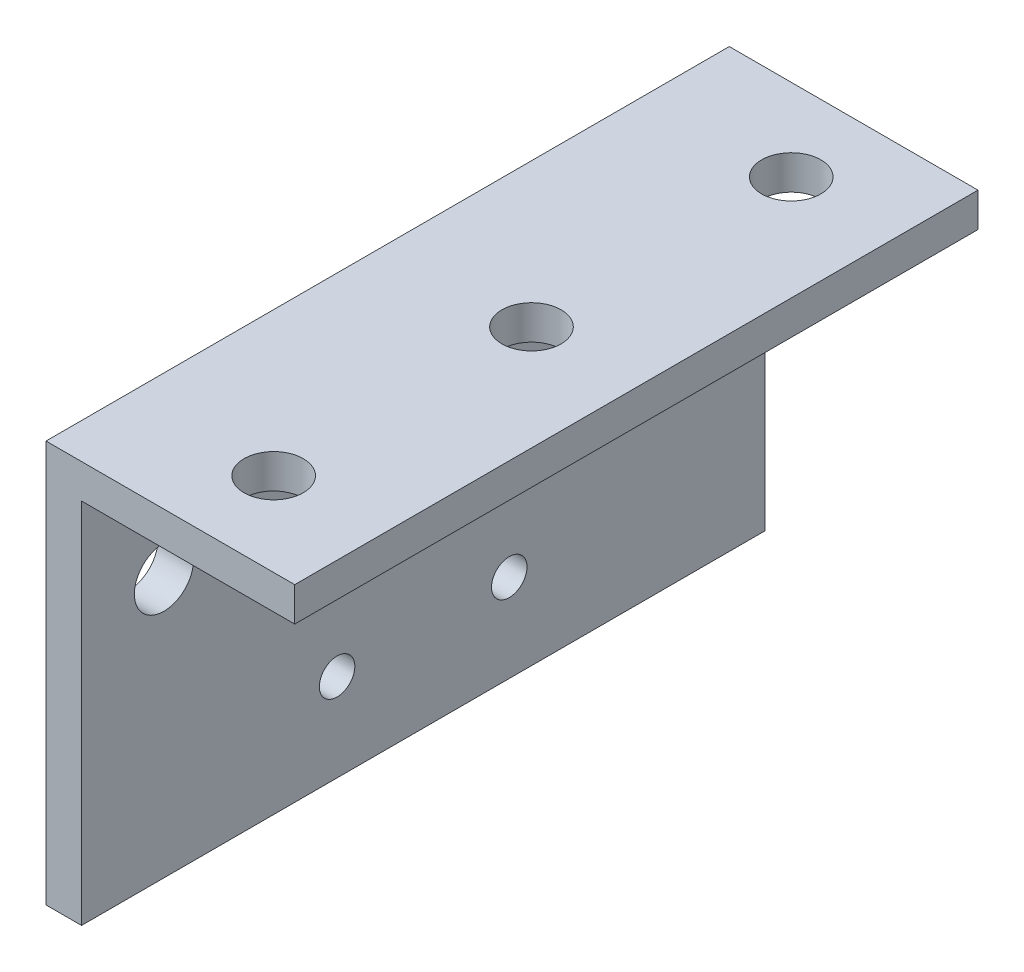
SolidWorks part; units mm, degrees
material "6061 Alloy"
ref_plane "Front Plane" through (0, 0, 0) normal (0, 0, 1) x (1, 0, 0)
ref_plane "Top Plane" through (0, 0, 0) normal (0, 1, 0) x (1, 0, 0)
ref_plane "Right Plane" through (0, 0, 0) normal (1, 0, 0) x (0, 0, -1)
sketch "Sketch1" plane through (0, 0, 0) normal (0, 0, 1) x (1, 0, 0)
  line L0 (0, 0) -> (0, 37.338)
  line L1 (0, 37.338) -> (23.114, 37.338)
  line L2 (23.114, 37.338) -> (23.114, 34.163)
  line L3 (0, 0) -> (3.302, 0)
  line L4 (3.302, 0) -> (3.302, 34.163)
  line L5 (3.302, 34.163) -> (23.114, 34.163)
  dimension "D1" = 37.338
  dimension "D2" = 23.114
  dimension "D3" = 3.175
extrude "Boss-Extrude1" add sketch "Sketch1" along normal blind 63.5
sketch "Sketch21" plane through (0, 0, 0) normal (-1, 0, 0) x (0, 0, 1)
  line L0 (31.75, 0) -> (31.75, 37.338) construction
  line L1 (63.5, 0) -> (0, 0) construction
  line L2 (63.5, 37.338) -> (0, 37.338) construction
  point P3 (31.75, 18.669)
sketch "Sketch28" plane through (0, 37.338, 0) normal (0, 1, 0) x (1, 0, 0)
  line L0 (23.114, -31.75) -> (0, -31.75) construction
  line L2 (23.114, -63.5) -> (23.114, 0) construction
  point P3 (11.557, -31.75)
sketch "Sketch29" plane through (0, 0, 0) normal (-1, 0, 0) x (0, 0, 1)
  line L0 (0, 24.2082) -> (63.5, 24.2082) construction
  line L1 (0, 37.338) -> (0, 0) construction
  line L2 (63.5, 37.338) -> (63.5, 0) construction
sketch "Sketch30" plane through (0, 37.338, 0) normal (0, 1, 0) x (1, 0, 0)
  line L0 (13.3686, 0) -> (13.3686, -63.5) construction
  line L1 (23.114, 0) -> (0, 0) construction
  line L2 (23.114, -63.5) -> (0, -63.5) construction
sketch "Sketch31" plane through (0, 0, 0) normal (-1, 0, 0) x (0, 0, 1)
  line L0 (31.75, 24.2082) -> (10.16, 24.2082) construction
  line L1 (0, 24.2082) -> (63.5, 24.2082) construction
  line L2 (31.75, 24.2082) -> (53.34, 24.2082) construction
sketch "Sketch32" plane through (0, 37.338, 0) normal (0, 1, 0) x (1, 0, 0)
  line L0 (13.3686, -31.75) -> (13.3686, -53.34) construction
  line L1 (13.3686, 0) -> (13.3686, -63.5) construction
  line L2 (13.3686, -31.75) -> (13.3686, -10.16) construction
hole_wizard "M5 Clearance Hole1" positions "Sketch35" profile "Sketch36" hole size "M5" standard "ANSI Metric" end condition through all
sketch "Sketch35" plane through (0, 0, 0) normal (-1, 0, 0) x (0, 0, 1)
  line L0 (0, 24.2082) -> (63.5, 24.2082) construction
  point P0 (55.8413, 24.2082)
sketch "Sketch36" plane through (0, 24.2082, 55.8413) normal (0, 1, 0) x (0, 0, 1)
  line L0 (0, 0) -> (0, 23.114)
  line L1 (0, 23.114) -> (2.75, 23.114)
  line L2 (2.75, 23.114) -> (2.75, 0)
  line L5 (2.75, 0) -> (0, 0)
  line L11 (0, -6.35) -> (0, 107.95) construction
  dimension "Thru Hole Dia." = 5.5
  dimension "Thru Hole Depth" = 23.114
hole_wizard "M5 Clearance Hole2" positions "Sketch37" profile "Sketch38" hole size "M5" standard "ANSI Metric" end condition through all
sketch "Sketch37" plane through (0, 0, 0) normal (-1, 0, 0) x (0, 0, 1)
  line L0 (0, 24.2082) -> (63.5, 24.2082) construction
  point P0 (7.6776, 24.2082)
sketch "Sketch38" plane through (0, 24.2082, 7.6776) normal (0, 1, 0) x (0, 0, 1)
  line L0 (0, 0) -> (0, 23.114)
  line L1 (0, 23.114) -> (2.75, 23.114)
  line L2 (2.75, 23.114) -> (2.75, 0)
  line L5 (2.75, 0) -> (0, 0)
  line L11 (0, -6.35) -> (0, 107.95) construction
  dimension "Thru Hole Dia." = 5.5
  dimension "Thru Hole Depth" = 23.114
hole_wizard "M5 Clearance Hole3" positions "Sketch39" profile "Sketch40" hole size "M5" standard "ANSI Metric" end condition through all
sketch "Sketch39" plane through (0, 37.338, 0) normal (0, 1, 0) x (1, 0, 0)
  point P0 (13.3686, -31.75)
sketch "Sketch40" plane through (13.3686, 37.338, 31.75) normal (1, 0, 0) x (0, 0, 1)
  line L0 (0, 0) -> (0, 37.338)
  line L1 (0, 37.338) -> (2.75, 37.338)
  line L2 (2.75, 37.338) -> (2.75, 0)
  line L5 (2.75, 0) -> (0, 0)
  line L11 (0, -6.35) -> (0, 107.95) construction
  dimension "Thru Hole Dia." = 5.5
  dimension "Thru Hole Depth" = 37.338
hole_wizard "M5 Clearance Hole4" positions "Sketch43" profile "Sketch44" hole size "M5" standard "ANSI Metric" end condition through all
sketch "Sketch43" plane through (0, 37.338, 0) normal (0, 1, 0) x (1, 0, 0)
  line L0 (13.3686, 0) -> (13.3686, -63.5) construction
  point P0 (13.3686, -55.7137)
sketch "Sketch44" plane through (13.3686, 37.338, 55.7137) normal (1, 0, 0) x (0, 0, 1)
  line L0 (0, 0) -> (0, 37.338)
  line L1 (0, 37.338) -> (2.75, 37.338)
  line L2 (2.75, 37.338) -> (2.75, 0)
  line L5 (2.75, 0) -> (0, 0)
  line L11 (0, -6.35) -> (0, 107.95) construction
  dimension "Thru Hole Dia." = 5.5
  dimension "Thru Hole Depth" = 37.338
hole_wizard "M5 Clearance Hole5" positions "Sketch49" profile "Sketch50" hole size "M5" standard "ANSI Metric" end condition through all
sketch "Sketch49" plane through (0, 37.338, 0) normal (0, 1, 0) x (1, 0, 0)
  line L0 (13.3686, 0) -> (13.3686, -63.5) construction
  point P0 (13.3686, -7.6106)
sketch "Sketch50" plane through (13.3686, 37.338, 7.6106) normal (1, 0, 0) x (0, 0, 1)
  line L0 (0, 0) -> (0, 37.338)
  line L1 (0, 37.338) -> (2.75, 37.338)
  line L2 (2.75, 37.338) -> (2.75, 0)
  line L5 (2.75, 0) -> (0, 0)
  line L11 (0, -6.35) -> (0, 107.95) construction
  dimension "Thru Hole Dia." = 5.5
  dimension "Thru Hole Depth" = 37.338
sketch "Sketch51" plane through (0, 0, 0) normal (-1, 0, 0) x (0, 0, 1)
  line L0 (63.5, 34.163) -> (0, 34.163) construction
  line L1 (39.75, 24.163) -> (23.75, 24.163) construction
  line L2 (39.75, 24.163) -> (39.75, 8.163) construction
  line L3 (39.75, 8.163) -> (23.75, 8.163) construction
  line L4 (23.75, 24.163) -> (23.75, 8.163) construction
  line L5 (39.75, 24.163) -> (23.75, 8.163) construction
  line L6 (39.75, 8.163) -> (23.75, 24.163) construction
  line L7 (31.75, 37.338) -> (31.75, 0) construction
  line L8 (63.5, 37.338) -> (0, 37.338) construction
  line L9 (63.5, 0) -> (0, 0) construction
  circle A0 centre (31.75, 16.163) radius 5 construction
  point P0 (31.75, 16.163)
  dimension "D4" = 10
  dimension "D1" = 10
  dimension "D2" = 16
  dimension "D3" = 16
hole_wizard "Tap Drill for M4x0.7 Tap2" positions "Sketch52" profile "Sketch53" hole size "M4x0.7" standard "ANSI Metric" end condition through all
sketch "Sketch52" plane through (0, 0, 0) normal (-1, 0, 0) x (0, 0, 1)
  point P0 (23.75, 24.163)
  point P3 (23.75, 8.163)
  point P6 (39.75, 8.163)
  point P9 (39.75, 24.163)
sketch "Sketch53" plane through (0, 24.163, 23.75) normal (0, 1, 0) x (0, 0, 1)
  line L0 (0, 0) -> (0, 23.114)
  line L1 (0, 23.114) -> (1.65, 23.114)
  line L2 (1.65, 23.114) -> (1.65, 0)
  line L5 (1.65, 0) -> (0, 0)
  line L11 (0, -6.35) -> (0, 107.95) construction
  dimension "Thru Hole Dia." = 3.3
  dimension "Thru Hole Depth" = 23.114
